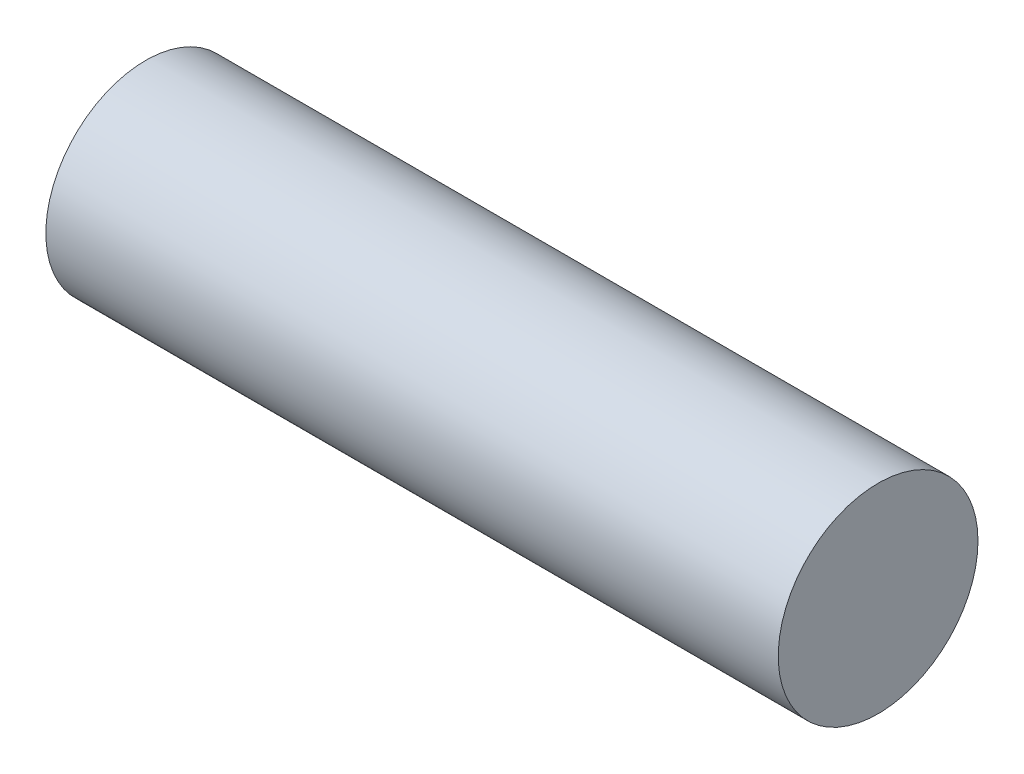
SolidWorks part; units mm, degrees
material "ABS"
ref_plane "Front Plane" through (0, 0, 0) normal (0, 0, 1) x (1, 0, 0)
ref_plane "Top Plane" through (0, 0, 0) normal (0, 1, 0) x (1, 0, 0)
ref_plane "Right Plane" through (0, 0, 0) normal (1, 0, 0) x (0, 0, -1)
sketch "Sketch1" plane through (0, 0, 0) normal (1, 0, 0) x (0, 0, -1)
  circle A0 centre (0, 0) radius 7.5
extrude "Boss-Extrude1" add sketch "Sketch1" along normal blind 55
